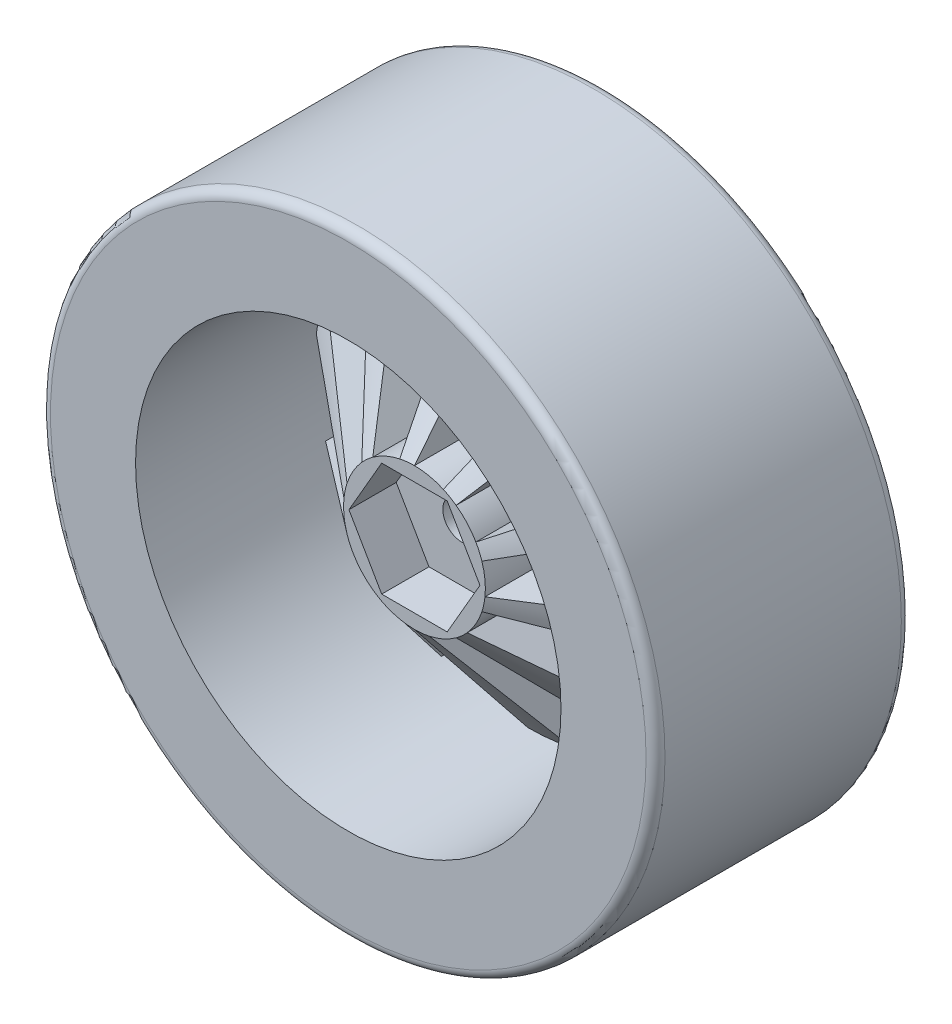
SolidWorks part; units mm, degrees
ref_plane "前视基准面" through (0, 0, 0) normal (0, 0, 1) x (1, 0, 0)
ref_plane "上视基准面" through (0, 0, 0) normal (0, 1, 0) x (1, 0, 0)
ref_plane "右视基准面" through (0, 0, 0) normal (1, 0, 0) x (0, 0, -1)
ref_axis "基准轴1" through (0, 0, -16.35) along (0, 0, 1)
sketch "草图1" plane through (0, 0, 0) normal (0, 0, 1) x (1, 0, 0)
  line L1 (-6.9282, 0) -> (-3.4641, -6)
  line L2 (-3.4641, -6) -> (3.4641, -6)
  line L3 (3.4641, -6) -> (6.9282, 0)
  line L4 (6.9282, 0) -> (3.4641, 6)
  line L5 (3.4641, 6) -> (-3.4641, 6)
  line L6 (-3.4641, 6) -> (-6.9282, 0)
  circle A2 centre (0, 0) radius 7.5
  circle A3 centre (0, 0) radius 6 construction
  dimension "D1" = 15
extrude "凸台-拉伸1" add sketch "草图1" along normal blind 5
sketch "草图2" plane through (0, 0, 0) normal (0, 0, 1) x (1, 0, 0)
  circle A0 centre (0, 0) radius 7.5
  circle A1 centre (0, 0) radius 2
extrude "凸台-拉伸2" add sketch "草图2" against normal blind 3
sketch "草图3" plane through (0, 0, 0) normal (0, 0, 1) x (1, 0, 0)
  circle A0 centre (0, 0) radius 32.5
  circle A1 centre (0, 0) radius 22.5
  dimension "D1" = 65
  dimension "D2" = 45
extrude "凸台-拉伸3" add sketch "草图3" along normal blind 12 and the other way blind 15 separate body
sketch "草图4" plane through (0, 0, 0) normal (1, 0, 0) x (0, 0, -1)
  line L4 (-5, 7.5) -> (3, 7.5)
  line L6 (15, 22.5) -> (3, 7.5)
  line L7 (-5, 7.5) -> (7, 22.5)
  line L8 (15, 22.5) -> (7, 22.5)
  dimension "D2" = 7.5
  dimension "D3" = 8
  dimension "D5" = 3
revolve "旋转1" add sketch "草图4" angle 12 about axis through (0, 0, -16.35) along (0, 0, 1)
pattern_circular "阵列(圆周)1" count 10 over 360 about axis through (0, 0, 0) along (0, 0, 1) of "旋转1"
sketch "草图5" plane through (0, 0, -3) normal (0, 0, -1) x (-1, 0, 0)
  circle A0 centre (0, 0) radius 4.5
  dimension "D1" = 9
extrude "切除-拉伸1" cut sketch "草图5" against normal blind 2
fillet "圆角1" radius 1 2 edges at (32.5, 0, 12) (32.5, 0, -15)
